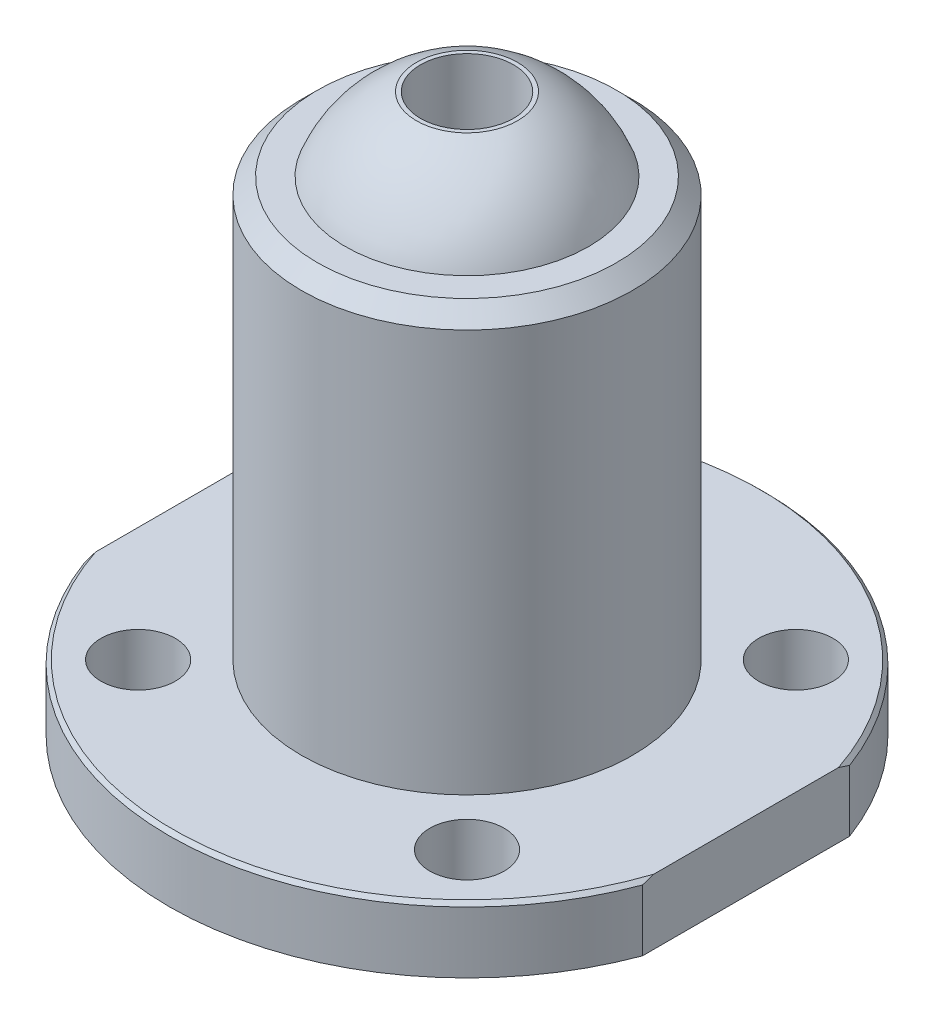
SolidWorks part; units mm, degrees
material "201 退火不锈钢 (SS)"
ref_plane "前视基准面" through (0, 0, 0) normal (0, 0, 1) x (1, 0, 0)
ref_plane "上视基准面" through (0, 0, 0) normal (0, 1, 0) x (1, 0, 0)
ref_plane "右视基准面" through (0, 0, 0) normal (1, 0, 0) x (0, 0, -1)
other "Configuration Table"
sketch "草图1" plane through (0, 0, 0) normal (0, 0, 1) x (1, 0, 0)
  line L0 (0, 33.5828) -> (0, -10.2614) construction
  line L1 (0, 0) -> (16, 0)
  line L2 (16, 0) -> (16, 3.5)
  line L3 (16, 3.5) -> (8.9, 3.5)
  line L4 (8.9, 3.5) -> (8.9, 25.1383)
  line L5 (8.9, 25.1383) -> (8.0383, 26)
  line L6 (8.0383, 26) -> (6.5383, 26)
  line L7 (0, 29.95) -> (2.7198, 29.95)
  line L8 (0, 0) -> (0, 29.95)
  arc A1 (6.5383, 26) -> (2.7198, 29.95) centre (0, 23.5) ccw
  point P13 (0, 33.5828)
  dimension "D1" = 8.9
  dimension "D4" = 14
  dimension "D2" = 16
  dimension "D3" = 23.5
  dimension "D5" = 3.5
  dimension "D6" = 26
  dimension "D7" = 135
  dimension "D8" = 1.5
  dimension "D9" = 29.95
revolve "旋转1" add sketch "草图1" angle 360 about L0
sketch "草图2" plane through (0, 29.95, 0) normal (0, 1, 0) x (1, 0, 0)
  circle A0 centre (0, 0) radius 2.5
  dimension "D1" = 5
extrude "切除-拉伸1" cut sketch "草图2" against normal blind 5
cosmetic thread "装饰螺纹线1" parameters "D2"=6
sketch "草图3" plane through (0, 3.5, 0) normal (0, 1, 0) x (1, 0, 0)
  line L0 (8.8388, 8.8388) -> (0, 0) construction
  line L1 (0, 0) -> (1.7272, 0) construction
  line L2 (-15, 5.5678) -> (-15, -5.5678)
  line L3 (0, -16.4725) -> (0, 16.4725) construction
  line L4 (15, 5.5678) -> (15, -5.5678)
  circle A0 centre (0, 0) radius 12.5 construction
  circle A1 centre (8.8388, 8.8388) radius 2
  circle A2 centre (8.8388, -8.8388) radius 2
  circle A3 centre (-8.8388, -8.8388) radius 2
  circle A4 centre (-8.8388, 8.8388) radius 2
  circle A5 centre (0, 0) radius 16 construction
  arc A6 (-15, 5.5678) -> (-15, -5.5678) centre (0, 0) ccw
  arc A7 (15, -5.5678) -> (15, 5.5678) centre (0, 0) ccw
  point P15 (0, 0)
  dimension "D1" = 25
  dimension "D3" = 4
  dimension "D2" = 45
  dimension "D5" = 15
  dimension "D4" = 4
extrude "切除-拉伸2" cut sketch "草图3" against normal blind 5
cosmetic thread "装饰螺纹线2" parameters "D2"=5
cosmetic thread "装饰螺纹线3" parameters "D2"=5
cosmetic thread "装饰螺纹线4" parameters "D2"=5
cosmetic thread "装饰螺纹线5" parameters "D2"=5
chamfer "倒角1" distance 0.2 angle 45 2 edges at (0, 3.5, 16) (0, 3.5, -16)
